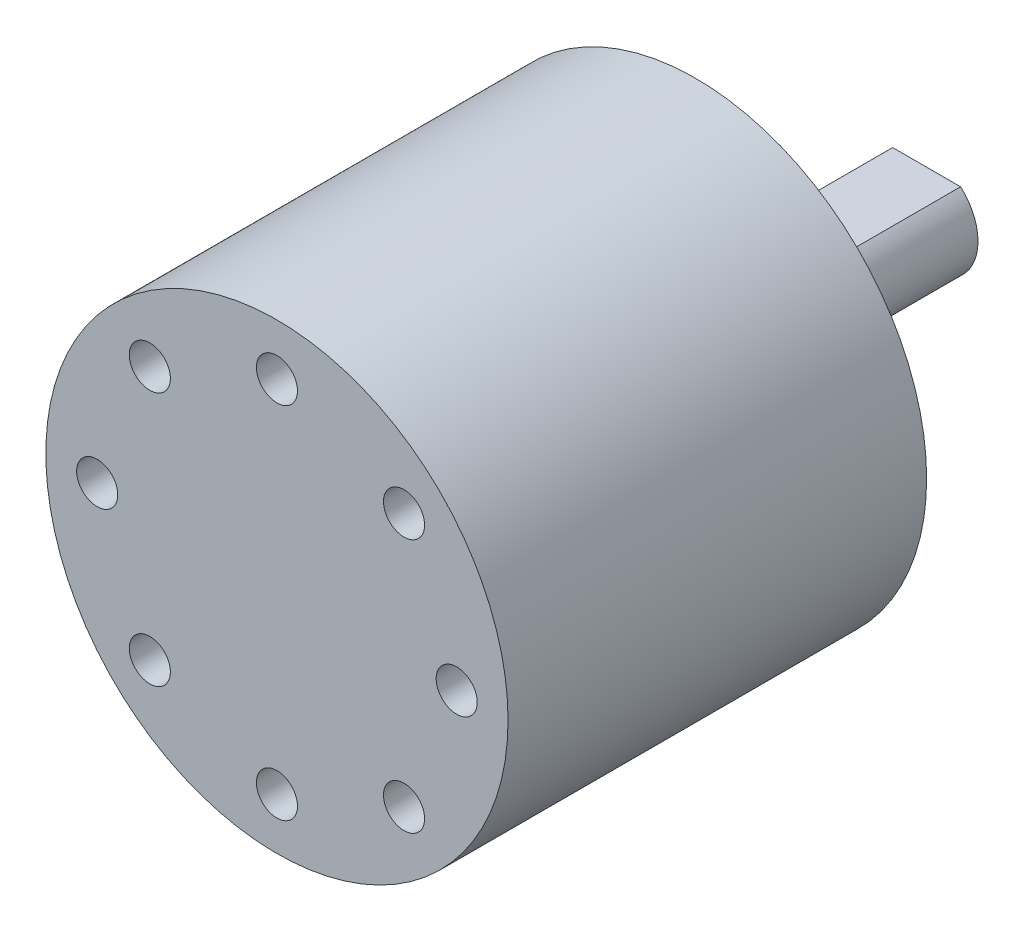
SolidWorks part; units mm, degrees
ref_plane "Front Plane" through (0, 0, 0) normal (0, 0, 1) x (1, 0, 0)
ref_plane "Top Plane" through (0, 0, 0) normal (0, 1, 0) x (1, 0, 0)
ref_plane "Right Plane" through (0, 0, 0) normal (1, 0, 0) x (0, 0, -1)
sketch "Sketch1" plane through (0, 0, 0) normal (0, 0, 1) x (1, 0, 0)
  circle A0 centre (0, 0) radius 18
  dimension "D1" = 36
extrude "Boss-Extrude1" add sketch "Sketch1" along normal blind 32.6
sketch "Sketch2" plane through (0, 0, 0) normal (0, 0, -1) x (-1, 0, 0)
  circle A0 centre (0, 0) radius 14 construction
  circle A1 centre (0, 14) radius 1.6
  dimension "D1" = 28
  dimension "D2" = 3.2
extrude "Cut-Extrude1" cut sketch "Sketch2" against normal through all
pattern_circular "CirPattern1" count 8 over 360 about axis through (0, 0, 0) along (0, 0, 1) of "Cut-Extrude1"
sketch "Sketch3" plane through (0, 0, 0) normal (0, 0, -1) x (-1, 0, 0)
  circle A0 centre (0, 0) radius 11
  dimension "D1" = 22
extrude "Boss-Extrude2" add sketch "Sketch3" along normal blind 2
sketch "Sketch4" plane through (0, 0, -2) normal (0, 0, -1) x (-1, 0, 0)
  circle A0 centre (0, 0) radius 4
  dimension "D1" = 8
extrude "Boss-Extrude3" add sketch "Sketch4" along normal blind 16
sketch "Sketch5" plane through (0, 0, -18) normal (0, 0, -1) x (-1, 0, 0)
  line L0 (-5, 3) -> (-2.6458, 3) construction
  line L1 (-2.6458, 3) -> (2.6458, 3)
  line L2 (-5, 3) -> (-5, -3) construction
  line L3 (-2.6458, -3) -> (2.6458, -3)
  line L4 (5, 3) -> (5, -3) construction
  line L5 (-5, 3) -> (5, -3) construction
  line L6 (-5, -3) -> (5, 3) construction
  line L7 (-5, -3) -> (-2.6458, -3) construction
  line L8 (2.6458, 3) -> (5, 3) construction
  line L9 (2.6458, -3) -> (5, -3) construction
  circle A0 centre (0, 0) radius 4 construction
  arc A1 (-3.43, 2.058) -> (-3.43, -2.058) centre (0, 0) ccw construction
  arc A2 (-2.6458, 3) -> (-3.43, 2.058) centre (0, 0) ccw construction
  arc A3 (-3.43, -2.058) -> (-2.6458, -3) centre (0, 0) ccw construction
  arc A4 (-2.6458, -3) -> (2.6458, -3) centre (0, 0) ccw
  arc A5 (2.6458, -3) -> (3.43, -2.058) centre (0, 0) ccw construction
  arc A6 (2.6458, 3) -> (-2.6458, 3) centre (0, 0) ccw
  arc A7 (3.43, -2.058) -> (3.43, 2.058) centre (0, 0) ccw construction
  arc A8 (3.43, 2.058) -> (2.6458, 3) centre (0, 0) ccw construction
  point P0 (0, 0)
  dimension "D1" = 6
  dimension "D2" = 10
extrude "Cut-Extrude2" cut sketch "Sketch5" against normal blind 15
